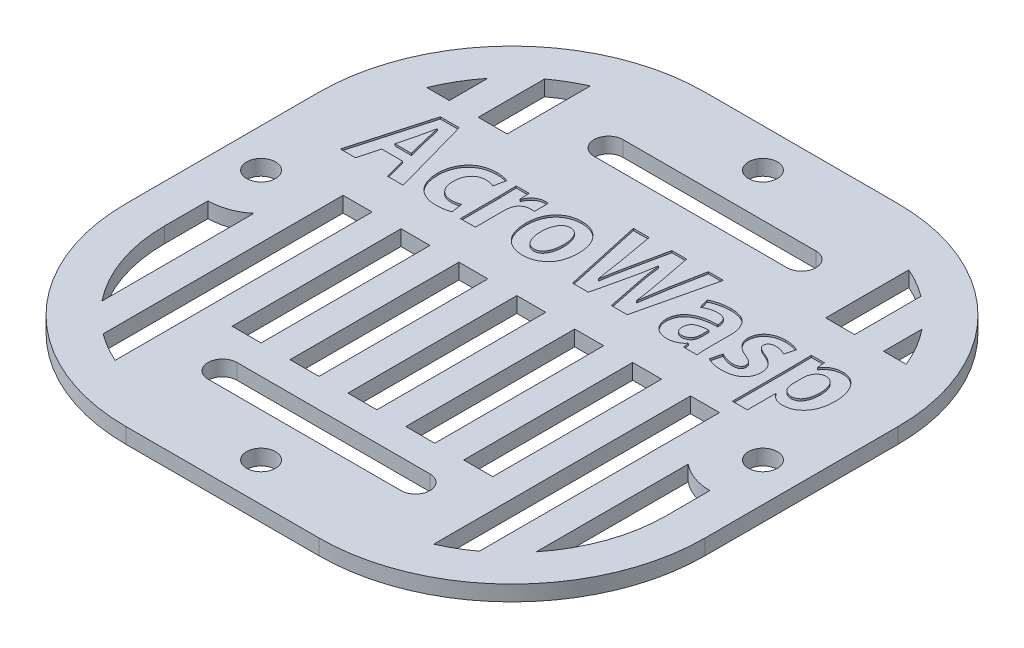
SolidWorks part; units mm, degrees
material "A-Glass Fiber"
ref_plane "Front Plane" through (0, 0, 0) normal (0, 0, 1) x (1, 0, 0)
ref_plane "Top Plane" through (0, 0, 0) normal (0, 1, 0) x (1, 0, 0)
ref_plane "Right Plane" through (0, 0, 0) normal (1, 0, 0) x (0, 0, -1)
sketch "Sketch1" plane through (0, 0, 0) normal (0, 1, 0) x (1, 0, 0)
  line L0 (0, 30) -> (0, -30) construction
  line L1 (-30, -30) -> (30, -30)
  line L2 (-30, -30) -> (-30, 30)
  line L3 (-30, 30) -> (30, 30)
  line L4 (30, -30) -> (30, 30)
  line L5 (-30, -30) -> (30, 30) construction
  line L6 (-30, 30) -> (30, -30) construction
  circle A0 centre (0, 26) radius 1.5
  circle A1 centre (26, 0) radius 1.5
  circle A2 centre (0, -26) radius 1.5
  circle A3 centre (-26, 0) radius 1.5
  point P0 (0, 0)
  point P19 (0, 0)
  dimension "D3" = 3
  dimension "D1" = 60
  dimension "D2" = 60
  dimension "D4" = 26
  dimension "D5" = 4
extrude "Boss-Extrude1" add sketch "Sketch1" along normal blind 1.6
fillet "Fillet1" radius 20 4 edges at (-30, 0.8, 30) (30, 0.8, 30) (30, 0.8, -30) (-30, 0.8, -30)
sketch "Sketch3" plane through (0, 1.6, 0) normal (0, 1, 0) x (1, 0, 0)
  text T0 "<b>AcroWasp</b>" font "@Adobe Gothic Std B" height in points 26
  dimension "D1" = 24
  dimension "D2" = 6
extrude "Cut-Extrude4" cut sketch "Sketch3" against normal blind 0.2
sketch "Sketch4" plane through (0, 1.6, 0) normal (0, 1, 0) x (1, 0, 0)
  line L0 (0, 30) -> (0, -30) construction
  line L1 (10, 30) -> (-10, 30) construction
  line L2 (-10, -30) -> (10, -30) construction
  line L3 (-30, 0) -> (30, 0) construction
  line L4 (-30, 10) -> (-30, -10) construction
  line L5 (30, -10) -> (30, 10) construction
  line L6 (-10, 20) -> (10, 20) construction
  line L7 (-10, 21.5) -> (10, 21.5)
  line L8 (-10, 18.5) -> (10, 18.5)
  line L9 (-10, -20) -> (10, -20) construction
  line L10 (-10, -21.5) -> (10, -21.5)
  line L11 (-10, -18.5) -> (10, -18.5)
  arc A0 (-10, 21.5) -> (-10, 18.5) centre (-10, 20) ccw
  arc A1 (10, 18.5) -> (10, 21.5) centre (10, 20) ccw
  arc A2 (-10, -21.5) -> (-10, -18.5) centre (-10, -20) cw
  arc A3 (10, -18.5) -> (10, -21.5) centre (10, -20) cw
  point P14 (0, 20)
  point P21 (0, -20)
  dimension "D1" = 3
  dimension "D2" = 20
  dimension "D3" = 20
extrude "Cut-Extrude5" cut sketch "Sketch4" against normal through all
sketch "Sketch6" plane through (0, 1.6, 0) normal (0, 1, 0) x (1, 0, 0)
  line L0 (-13.5, -15.5) -> (13.5, -15.5)
  line L1 (10, -18.5) -> (-10, -18.5) construction
  line L12 (-4.5, -33.6745) -> (-4.5, 33.6745)
  line L13 (-36.477, 16) -> (36.477, 16)
  line L14 (-36.477, 16) -> (-36.477, 2)
  line L15 (-36.477, 2) -> (36.477, 2)
  line L16 (-26, 10) -> (-26, -10)
  line L17 (-10, -26) -> (10, -26)
  line L18 (26, -10) -> (26, 10)
  line L19 (10, 26) -> (-10, 26)
  line L20 (-26, 10) -> (-26, -10)
  line L21 (-10, -26) -> (10, -26)
  line L22 (26, -10) -> (26, 10)
  line L23 (10, 26) -> (-10, 26)
  line L24 (36.477, 16) -> (36.477, 2)
  line L25 (-36.477, 16) -> (36.477, 2) construction
  line L26 (-36.477, 2) -> (36.477, 16) construction
  line L27 (-1.5, -33.6745) -> (1.5, -33.6745)
  line L28 (-1.5, -33.6745) -> (-1.5, 33.6745)
  line L29 (-1.5, 33.6745) -> (1.5, 33.6745)
  line L30 (1.5, -33.6745) -> (1.5, 33.6745)
  line L31 (-1.5, -33.6745) -> (1.5, 33.6745) construction
  line L32 (-1.5, 33.6745) -> (1.5, -33.6745) construction
  line L33 (-1.5, -33.6745) -> (-1.5, 33.6745)
  line L34 (-7.5, -33.6745) -> (-7.5, 33.6745)
  line L35 (-4.5, -33.6745) -> (-4.5, 33.6745)
  line L36 (-10.5, -33.6745) -> (-10.5, 33.6745)
  line L37 (-7.5, -33.6745) -> (-7.5, 33.6745)
  line L38 (-13.5, -33.1446) -> (-13.5, 34.2043)
  line L39 (-10.5, -33.6745) -> (-10.5, 33.6745)
  line L40 (-16.5, -33.6745) -> (-16.5, 33.6745)
  line L41 (-13.5, -33.1446) -> (-13.5, 34.2043)
  line L42 (-19.5, -33.6745) -> (-19.5, 33.6745)
  line L43 (-16.5, -33.6745) -> (-16.5, 33.6745)
  line L44 (-22.5, -33.6745) -> (-22.5, 33.6745)
  line L45 (-19.5, -33.6745) -> (-19.5, 33.6745)
  line L46 (-1.5, -33.6745) -> (-1.5, 33.6745)
  line L47 (1.5, -33.6745) -> (1.5, 33.6745)
  line L48 (-4.5, -33.6745) -> (-4.5, 33.6745)
  line L49 (-1.5, -33.6745) -> (-1.5, 33.6745)
  line L50 (-7.5, -33.6745) -> (-7.5, 33.6745)
  line L51 (-4.5, -33.6745) -> (-4.5, 33.6745)
  line L52 (-10.5, -33.6745) -> (-10.5, 33.6745)
  line L53 (-7.5, -33.6745) -> (-7.5, 33.6745)
  line L54 (-13.5, -33.1446) -> (-13.5, 34.2043)
  line L55 (-10.5, -33.6745) -> (-10.5, 33.6745)
  line L56 (-16.5, -33.6745) -> (-16.5, 33.6745)
  line L57 (-13.5, -33.1446) -> (-13.5, 34.2043)
  line L58 (-19.5, -33.6745) -> (-19.5, 33.6745)
  line L59 (-16.5, -33.6745) -> (-16.5, 33.6745)
  line L60 (1.5, -33.6745) -> (1.5, 33.6745)
  line L61 (4.5, -33.6745) -> (4.5, 33.6745)
  line L62 (-1.5, -33.6745) -> (-1.5, 33.6745)
  line L63 (1.5, -33.6745) -> (1.5, 33.6745)
  line L64 (-4.5, -33.6745) -> (-4.5, 33.6745)
  line L65 (-1.5, -33.6745) -> (-1.5, 33.6745)
  line L66 (-7.5, -33.6745) -> (-7.5, 33.6745)
  line L67 (-4.5, -33.6745) -> (-4.5, 33.6745)
  line L68 (-10.5, -33.6745) -> (-10.5, 33.6745)
  line L69 (-7.5, -33.6745) -> (-7.5, 33.6745)
  line L70 (-13.5, -33.1446) -> (-13.5, 34.2043)
  line L71 (-10.5, -33.6745) -> (-10.5, 33.6745)
  line L72 (-16.5, -33.6745) -> (-16.5, 33.6745)
  line L73 (-13.5, -33.1446) -> (-13.5, 34.2043)
  line L74 (4.5, -33.6745) -> (4.5, 33.6745)
  line L75 (7.5, -33.6745) -> (7.5, 33.6745)
  line L76 (1.5, -33.6745) -> (1.5, 33.6745)
  line L77 (4.5, -33.6745) -> (4.5, 33.6745)
  line L78 (-1.5, -33.6745) -> (-1.5, 33.6745)
  line L79 (1.5, -33.6745) -> (1.5, 33.6745)
  line L80 (-4.5, -33.6745) -> (-4.5, 33.6745)
  line L81 (-1.5, -33.6745) -> (-1.5, 33.6745)
  line L82 (-7.5, -33.6745) -> (-7.5, 33.6745)
  line L83 (-4.5, -33.6745) -> (-4.5, 33.6745)
  line L84 (-10.5, -33.6745) -> (-10.5, 33.6745)
  line L85 (-7.5, -33.6745) -> (-7.5, 33.6745)
  line L86 (-13.5, -33.1446) -> (-13.5, 34.2043)
  line L87 (-10.5, -33.6745) -> (-10.5, 33.6745)
  line L88 (7.5, -33.6745) -> (7.5, 33.6745)
  line L89 (10.5, -33.6745) -> (10.5, 33.6745)
  line L90 (4.5, -33.6745) -> (4.5, 33.6745)
  line L91 (7.5, -33.6745) -> (7.5, 33.6745)
  line L92 (1.5, -33.6745) -> (1.5, 33.6745)
  line L93 (4.5, -33.6745) -> (4.5, 33.6745)
  line L94 (-1.5, -33.6745) -> (-1.5, 33.6745)
  line L95 (1.5, -33.6745) -> (1.5, 33.6745)
  line L96 (-4.5, -33.6745) -> (-4.5, 33.6745)
  line L97 (-1.5, -33.6745) -> (-1.5, 33.6745)
  line L98 (-7.5, -33.6745) -> (-7.5, 33.6745)
  line L99 (-4.5, -33.6745) -> (-4.5, 33.6745)
  line L100 (-10.5, -33.6745) -> (-10.5, 33.6745)
  line L101 (-7.5, -33.6745) -> (-7.5, 33.6745)
  line L102 (10.5, -33.6745) -> (10.5, 33.6745)
  line L103 (13.5, -33.1446) -> (13.5, 34.2043)
  line L104 (7.5, -33.6745) -> (7.5, 33.6745)
  line L105 (10.5, -33.6745) -> (10.5, 33.6745)
  line L106 (4.5, -33.6745) -> (4.5, 33.6745)
  line L107 (7.5, -33.6745) -> (7.5, 33.6745)
  line L108 (1.5, -33.6745) -> (1.5, 33.6745)
  line L109 (4.5, -33.6745) -> (4.5, 33.6745)
  line L110 (-1.5, -33.6745) -> (-1.5, 33.6745)
  line L111 (1.5, -33.6745) -> (1.5, 33.6745)
  line L112 (-4.5, -33.6745) -> (-4.5, 33.6745)
  line L113 (-1.5, -33.6745) -> (-1.5, 33.6745)
  line L114 (-7.5, -33.6745) -> (-7.5, 33.6745)
  line L115 (-4.5, -33.6745) -> (-4.5, 33.6745)
  line L116 (13.5, -33.1446) -> (13.5, 34.2043)
  line L117 (16.5, -33.6745) -> (16.5, 33.6745)
  line L118 (10.5, -33.6745) -> (10.5, 33.6745)
  line L119 (13.5, -33.1446) -> (13.5, 34.2043)
  line L120 (7.5, -33.6745) -> (7.5, 33.6745)
  line L121 (10.5, -33.6745) -> (10.5, 33.6745)
  line L122 (4.5, -33.6745) -> (4.5, 33.6745)
  line L123 (7.5, -33.6745) -> (7.5, 33.6745)
  line L124 (1.5, -33.6745) -> (1.5, 33.6745)
  line L125 (4.5, -33.6745) -> (4.5, 33.6745)
  line L126 (-1.5, -33.6745) -> (-1.5, 33.6745)
  line L127 (1.5, -33.6745) -> (1.5, 33.6745)
  line L128 (-4.5, -33.6745) -> (-4.5, 33.6745)
  line L129 (-1.5, -33.6745) -> (-1.5, 33.6745)
  line L130 (16.5, -33.6745) -> (16.5, 33.6745)
  line L131 (19.5, -33.6745) -> (19.5, 33.6745)
  line L132 (13.5, -33.1446) -> (13.5, 34.2043)
  line L133 (16.5, -33.6745) -> (16.5, 33.6745)
  line L134 (10.5, -33.6745) -> (10.5, 33.6745)
  line L135 (13.5, -33.1446) -> (13.5, 34.2043)
  line L136 (7.5, -33.6745) -> (7.5, 33.6745)
  line L137 (10.5, -33.6745) -> (10.5, 33.6745)
  line L138 (4.5, -33.6745) -> (4.5, 33.6745)
  line L139 (7.5, -33.6745) -> (7.5, 33.6745)
  line L140 (1.5, -33.6745) -> (1.5, 33.6745)
  line L141 (4.5, -33.6745) -> (4.5, 33.6745)
  line L142 (-1.5, -33.6745) -> (-1.5, 33.6745)
  line L143 (1.5, -33.6745) -> (1.5, 33.6745)
  line L144 (1.5, -33.6745) -> (1.5, 33.6745)
  line L145 (4.5, -33.6745) -> (4.5, 33.6745)
  line L146 (4.5, -33.6745) -> (4.5, 33.6745)
  line L147 (7.5, -33.6745) -> (7.5, 33.6745)
  line L148 (7.5, -33.6745) -> (7.5, 33.6745)
  line L149 (10.5, -33.6745) -> (10.5, 33.6745)
  line L150 (10.5, -33.6745) -> (10.5, 33.6745)
  line L151 (13.5, -33.1446) -> (13.5, 34.2043)
  line L152 (13.5, -33.1446) -> (13.5, 34.2043)
  line L153 (16.5, -33.6745) -> (16.5, 33.6745)
  line L154 (16.5, -33.6745) -> (16.5, 33.6745)
  line L155 (19.5, -33.6745) -> (19.5, 33.6745)
  line L156 (19.5, -33.6745) -> (19.5, 33.6745)
  line L157 (22.5, -33.6745) -> (22.5, 33.6745)
  arc A17 (-26, -10) -> (-10, -26) centre (-10, -10) ccw
  arc A18 (10, -26) -> (26, -10) centre (10, -10) ccw
  arc A19 (26, 10) -> (10, 26) centre (10, 10) ccw
  arc A20 (-10, 26) -> (-26, 10) centre (-10, 10) ccw
  arc A21 (-26, -10) -> (-10, -26) centre (-10, -10) ccw
  arc A22 (10, -26) -> (26, -10) centre (10, -10) ccw
  arc A23 (26, 10) -> (10, 26) centre (10, 10) ccw
  arc A24 (-10, 26) -> (-26, 10) centre (-10, 10) ccw
  circle A26 centre (-26, 0) radius 5.5
  circle A27 centre (-26, 0) radius 5.5
  circle A29 centre (26, 0) radius 5.5
  circle A30 centre (26, 0) radius 5.5
  point P0 (0, 9)
  point P11 (0, 0)
  dimension "D4" = 14
  dimension "D5" = 9
  dimension "D6" = 3
  dimension "D7" = 3
  dimension "D1" = 4
  dimension "D2" = 4
  dimension "D3" = 4
extrude "Cut-Extrude6" cut sketch "Sketch6" against normal through all contours L0 L30 L15 L28 | L0 L75 L15 L61 | L0 L103 L15 L89 | L154 A22 L156 L15 | L131 A23 L117 L13 | A30 L157 A22 L22 | L13 A23 L157 | L34 L0 L12 L15 | L38 L0 L36 L15 | L58 A21 L72 L15 | L40 A24 L42 L13 | L44 A24 L13 | A27 L20 A21 L44
